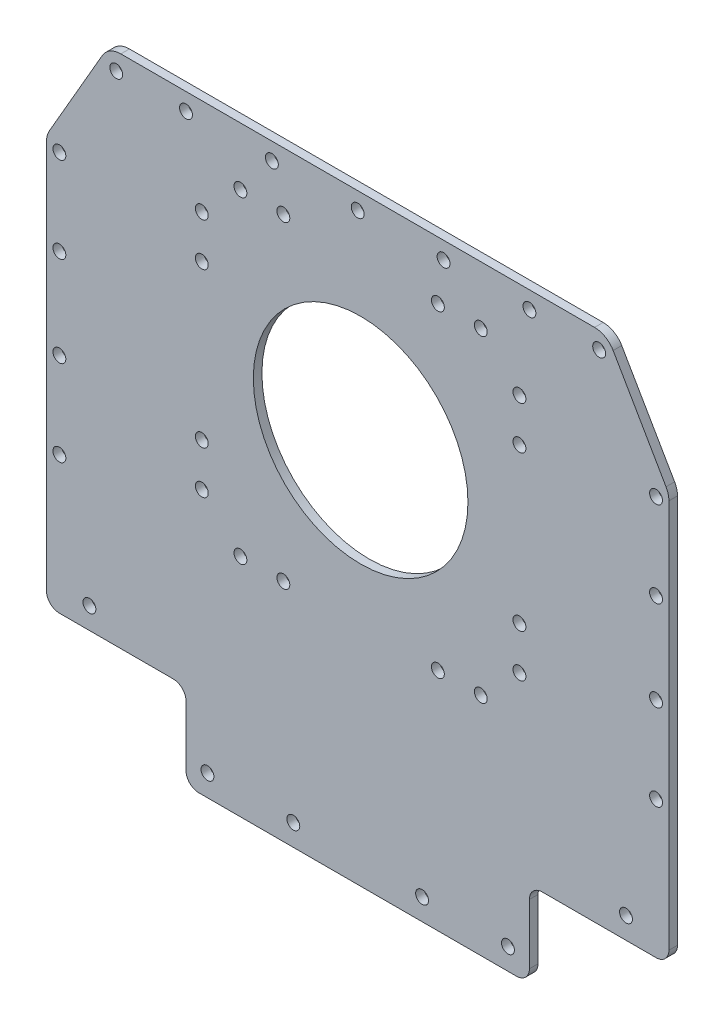
SolidWorks part; units mm, degrees
material "Thornel Mat VMA"
ref_plane "前视基准面" through (0, 0, 0) normal (0, 0, 1) x (1, 0, 0)
ref_plane "上视基准面" through (0, 0, 0) normal (0, 1, 0) x (1, 0, 0)
ref_plane "右视基准面" through (0, 0, 0) normal (1, 0, 0) x (0, 0, -1)
other "Configuration Table"
sketch "草图1" plane through (0, 0, 0) normal (0, 0, 1) x (1, 0, 0)
  line L0 (-60.1918, 67.5) -> (-72.5123, 46.1603)
  line L5 (0, 0) -> (0, 20) construction
  line L6 (-40.0334, 60.2469) -> (-40.0052, 60.2469) construction
  line L7 (-73.1822, 43.6603) -> (-73.1822, -47)
  line L8 (-70.1822, -50) -> (-43.6822, -50)
  line L9 (-40.6822, -53) -> (-40.6822, -67)
  line L10 (-37.6822, -70) -> (36.3178, -70)
  line L11 (39.3178, -67) -> (39.3178, -53)
  line L12 (42.3178, -50) -> (68.8178, -50)
  line L13 (71.8178, -47) -> (71.8178, 43.6603)
  line L14 (71.148, 46.1603) -> (58.8275, 67.5)
  line L15 (54.4973, 70) -> (-55.8616, 70)
  line L20 (-40.0334, -19.7531) -> (-40.0052, -19.7531) construction
  line L21 (-40.0334, 60.2469) -> (39.9666, -19.7531) construction
  line L22 (-40.0334, -19.7531) -> (39.9666, 60.2469) construction
  line L23 (39.9948, 60.2469) -> (39.9666, 60.2469)
  line L24 (-40.0052, 60.2469) -> (-40.0052, 60.2187)
  line L25 (39.9666, -19.7531) -> (39.9948, -19.7531)
  line L26 (-40.0052, -19.725) -> (-40.0052, -19.7531)
  circle A0 centre (-0.6822, 66) radius 1.5
  circle A1 centre (-20.6822, 66) radius 1.5
  circle A2 centre (19.3178, 66) radius 1.5
  circle A3 centre (39.3178, 66) radius 1.5
  arc A4 (-72.5123, 46.1603) -> (-73.1822, 43.6603) centre (-68.1822, 43.6603) ccw
  arc A5 (-73.1822, -47) -> (-70.1822, -50) centre (-70.1822, -47) ccw
  arc A6 (-40.6822, -53) -> (-43.6822, -50) centre (-43.6822, -53) ccw
  arc A7 (-40.6822, -67) -> (-37.6822, -70) centre (-37.6822, -67) ccw
  arc A8 (36.3178, -70) -> (39.3178, -67) centre (36.3178, -67) ccw
  arc A9 (42.3178, -50) -> (39.3178, -53) centre (42.3178, -53) ccw
  arc A10 (68.8178, -50) -> (71.8178, -47) centre (68.8178, -47) ccw
  arc A11 (71.8178, 43.6603) -> (71.148, 46.1603) centre (66.8178, 43.6603) ccw
  arc A12 (58.8275, 67.5) -> (54.4973, 70) centre (54.4973, 65) ccw
  arc A13 (-55.8616, 70) -> (-60.1918, 67.5) centre (-55.8616, 65) ccw
  circle A14 centre (55.5678, 66) radius 1.5
  circle A15 centre (68.8178, 43) radius 1.5
  circle A16 centre (68.8178, 23) radius 1.5
  circle A17 centre (68.8178, 2) radius 1.5
  circle A18 centre (68.8178, -18) radius 1.5
  circle A19 centre (61.8178, -45) radius 1.5
  circle A20 centre (34.3178, -65) radius 1.5
  circle A21 centre (14.3178, -65) radius 1.5
  circle A22 centre (-15.6822, -65) radius 1.5
  circle A23 centre (-35.6822, -65) radius 1.5
  circle A24 centre (-63.1822, -45) radius 1.5
  circle A25 centre (-70.1822, -18) radius 1.5
  circle A26 centre (-70.1822, 2) radius 1.5
  circle A27 centre (-70.1822, 23) radius 1.5
  circle A28 centre (-70.1822, 43) radius 1.5
  circle A29 centre (-40.6822, 66) radius 1.5
  circle A30 centre (-56.9322, 66) radius 1.5
  circle A47 centre (-37.0052, 37.5382) radius 1.5
  circle A48 centre (17.9948, 56.5382) radius 1.5
  circle A49 centre (27.9948, 56.5382) radius 1.5
  circle A50 centre (36.9948, 47.5382) radius 1.5
  circle A51 centre (36.9948, 37.5382) radius 1.5
  circle A52 centre (36.9948, 1.5382) radius 1.5
  circle A53 centre (36.9948, -8.4618) radius 1.5
  circle A54 centre (27.9948, -17.4618) radius 1.5
  circle A55 centre (17.9948, -17.4618) radius 1.5
  circle A56 centre (-18.0052, -17.4618) radius 1.5
  circle A57 centre (-28.0052, -17.4618) radius 1.5
  circle A58 centre (-37.0052, -8.4618) radius 1.5
  circle A59 centre (-37.0052, 1.5382) radius 1.5
  circle A60 centre (-18.0052, 56.5382) radius 1.5
  circle A61 centre (-28.0052, 56.5382) radius 1.5
  circle A62 centre (-37.0052, 47.5382) radius 1.5
  point P2 (0, 0)
  point P3 (-0.0334, 20.2469)
  dimension "D1" = 20
  dimension "D2" = 80
  dimension "D3" = 40
extrude "凸台-拉伸1" add sketch "草图1" along normal blind 2
sketch "草图2" plane through (0, 0, 2) normal (0, 0, 1) x (1, 0, 0)
  circle A0 centre (0, 20) radius 25
  point P3 (0, 0)
  point P4 (0, 18.6357)
  dimension "D1" = 20
extrude "切除-拉伸1" cut sketch "草图2" against normal blind 2
